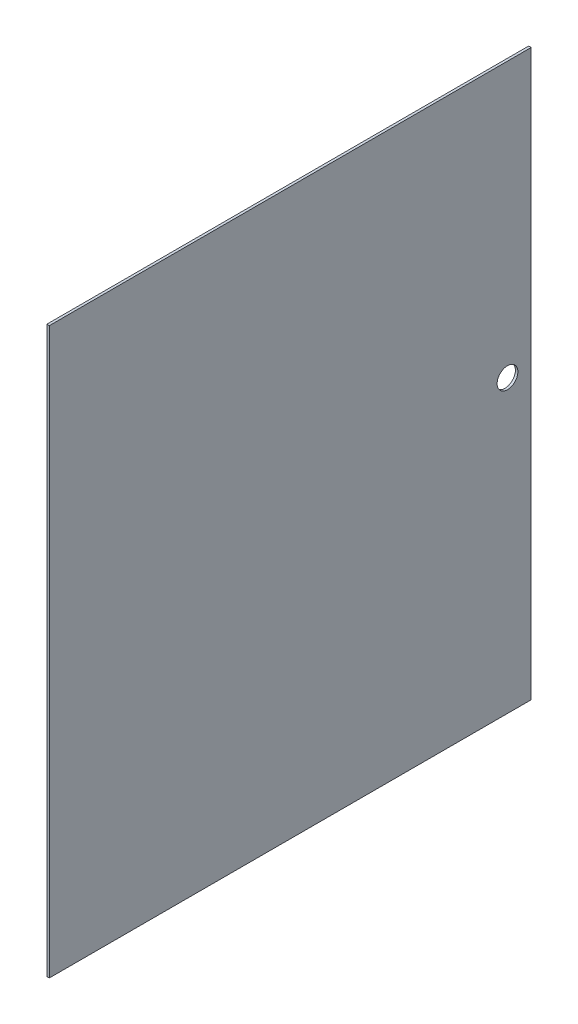
SolidWorks part; units mm, degrees
ref_plane "Alzado" through (0, 0, 0) normal (0, 0, 1) x (1, 0, 0)
ref_plane "Planta" through (0, 0, 0) normal (0, 1, 0) x (1, 0, 0)
ref_plane "Vista lateral" through (0, 0, 0) normal (1, 0, 0) x (0, 0, -1)
sketch "Croquis1" plane through (0, 0, 0) normal (1, 0, 0) x (0, 0, -1)
  line L1 (290, -340) -> (-290, -340)
  line L2 (290, -340) -> (290, 340)
  line L3 (290, 340) -> (-290, 340)
  line L4 (-290, -340) -> (-290, 340)
  line L5 (290, -340) -> (-290, 340) construction
  line L6 (290, 340) -> (-290, -340) construction
  point P0 (0, 0)
  dimension "D1" = 680
  dimension "D2" = 580
extrude "Saliente-Extruir1" add sketch "Croquis1" along normal blind 3
sketch "Croquis2" plane through (0, 0, 0) normal (-1, 0, 0) x (0, 0, 1)
  line L0 (-290, -340) -> (-290, 340) construction
  line L1 (-290, 340) -> (290, 340) construction
  circle A0 centre (-261.5, 10) radius 12.5
  dimension "D1" = 25
  dimension "D2" = 28.5
  dimension "D3" = 330
extrude "Cortar-Extruir1" cut sketch "Croquis2" against normal up to next
